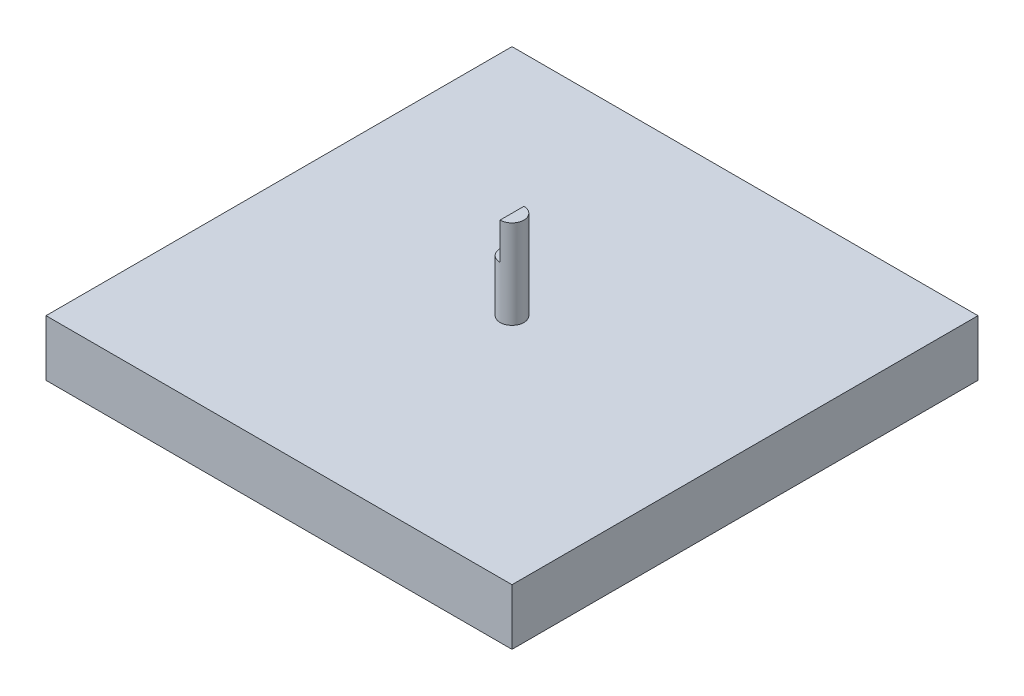
SolidWorks part; units mm, degrees
ref_plane "Front Plane" through (0, 0, 0) normal (0, 0, 1) x (1, 0, 0)
ref_plane "Top Plane" through (0, 0, 0) normal (0, 1, 0) x (1, 0, 0)
ref_plane "Right Plane" through (0, 0, 0) normal (1, 0, 0) x (0, 0, -1)
sketch "Sketch1" plane through (0, 0, 0) normal (0, 1, 0) x (1, 0, 0)
  line L1 (0, 0) -> (94, 0)
  line L2 (0, 0) -> (0, 94)
  line L3 (0, 94) -> (94, 94)
  line L4 (94, 0) -> (94, 94)
  dimension "D1" = 94
  dimension "D2" = 94
extrude "Boss-Extrude1" add sketch "Sketch1" along normal blind 11.3
sketch "Sketch2" plane through (0, 0, 0) normal (0, -1, 0) x (1, 0, 0)
  line L0 (0, 0) -> (94, 0) construction
  line L1 (0, -94) -> (0, 0) construction
  line L2 (0, -47) -> (94, -47) construction
  line L3 (94, 0) -> (94, -94) construction
  line L4 (47, 0) -> (47, -94) construction
  line L5 (94, -94) -> (0, -94) construction
  circle A0 centre (6.4, -6.4) radius 1.9
  circle A1 centre (6.4, -87.6) radius 1.9
  circle A2 centre (87.6, -87.6) radius 1.9
  circle A3 centre (87.6, -6.4) radius 1.9
  dimension "D1" = 3.8
  dimension "D2" = 6.4
  dimension "D3" = 6.4
extrude "Boss-Extrude2" add sketch "Sketch2" along normal blind 2
sketch "Sketch3" plane through (0, 11.3, 0) normal (0, 1, 0) x (1, 0, 0)
  line L0 (0, 47) -> (94, 47) construction
  line L1 (0, 94) -> (0, 0) construction
  line L2 (94, 0) -> (94, 94) construction
  circle A0 centre (47, 47) radius 2.4
  dimension "D1" = 4.8
extrude "Boss-Extrude3" add sketch "Sketch3" along normal blind 17.9
sketch "Sketch4" plane through (0, 29.2, 0) normal (0, 1, 0) x (1, 0, 0)
  line L0 (0, 94) -> (0, 0) construction
  line L1 (47, 49.4) -> (43, 49.4)
  line L2 (47, 49.4) -> (47, 42.4)
  line L3 (47, 42.4) -> (43, 42.4)
  line L4 (43, 49.4) -> (43, 42.4)
  circle A0 centre (47, 47) radius 2.4 construction
  circle A1 centre (47, 47) radius 2.4 construction
  dimension "D1" = 7
  dimension "D2" = 4
  dimension "D3" = 43
extrude "Cut-Extrude1" cut sketch "Sketch4" against normal blind 7.4
